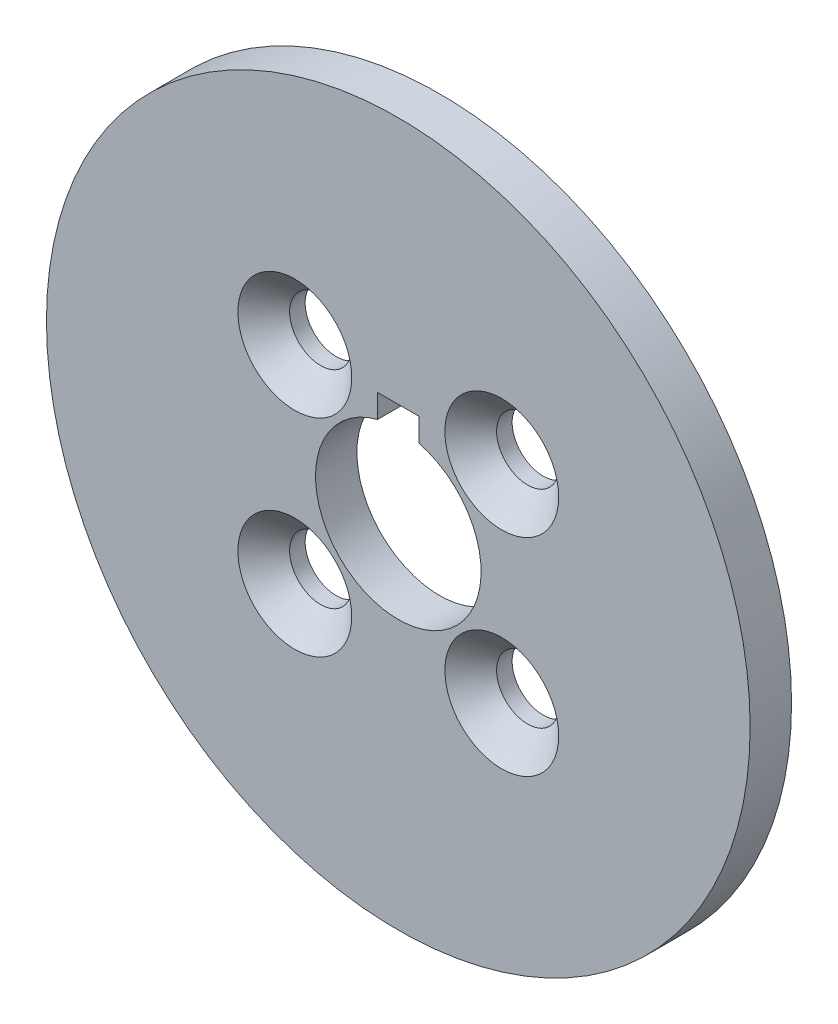
SolidWorks part; units mm, degrees
material "AISI 316 Annealed Stainless Steel Bar (SS)"
ref_plane "Front Plane" through (0, 0, 0) normal (0, 0, 1) x (1, 0, 0)
ref_plane "Top Plane" through (0, 0, 0) normal (0, 1, 0) x (1, 0, 0)
ref_plane "Right Plane" through (0, 0, 0) normal (1, 0, 0) x (0, 0, -1)
sketch "Sketch1" plane through (0, 0, 0) normal (0, 0, 1) x (1, 0, 0)
  line L0 (-1, 3.873) -> (-1, 5.003)
  line L1 (-1, 5.003) -> (1, 5.003)
  line L2 (1, 5.003) -> (1, 3.873)
  circle A0 centre (0, 0) radius 17
  arc A1 (-1, 3.873) -> (1, 3.873) centre (0, 0) ccw
  dimension "D1" = 34
  dimension "D2" = 8
  dimension "D3" = 1
  dimension "D4" = 2
  dimension "D5" = 1.13
extrude "Boss-Extrude1" add sketch "Sketch1" along normal blind 2
hole_wizard "CSK for M2.5 Flat Head Machine Screw1" positions "Sketch3" profile "Sketch4" countersink size "M2.5" standard "ANSI Metric" end condition through all
sketch "Sketch3" plane through (0, 0, 2) normal (0, 0, 1) x (1, 0, 0)
  point P0 (5, 5)
  dimension "D1" = 5
  dimension "D2" = 5
sketch "Sketch4" plane through (5, 5, 2) normal (1, 0, 0) x (0, -1, 0)
  line L0 (0, 0) -> (0, 2)
  line L1 (0, 2) -> (1.5, 2)
  line L2 (1.5, 2) -> (1.5, 1.25)
  line L3 (1.5, 1.25) -> (2.75, 0)
  line L5 (2.75, 0) -> (0, 0)
  line L6 (-1.5, 1.25) -> (-2.75, 0) construction
  line L11 (0, -6.35) -> (0, 107.95) construction
  dimension "Thru Hole Dia." = 3
  dimension "Thru Hole Depth" = 2
  dimension "Near C'Sink Dia." = 5.5
  dimension "Near C'Sink Angle" = 90
pattern_circular "CirPattern1" count 4 over 360 about axis through (0, 0, 0) along (0, 0, 1) of "CSK for M2.5 Flat Head Machine Screw1"
